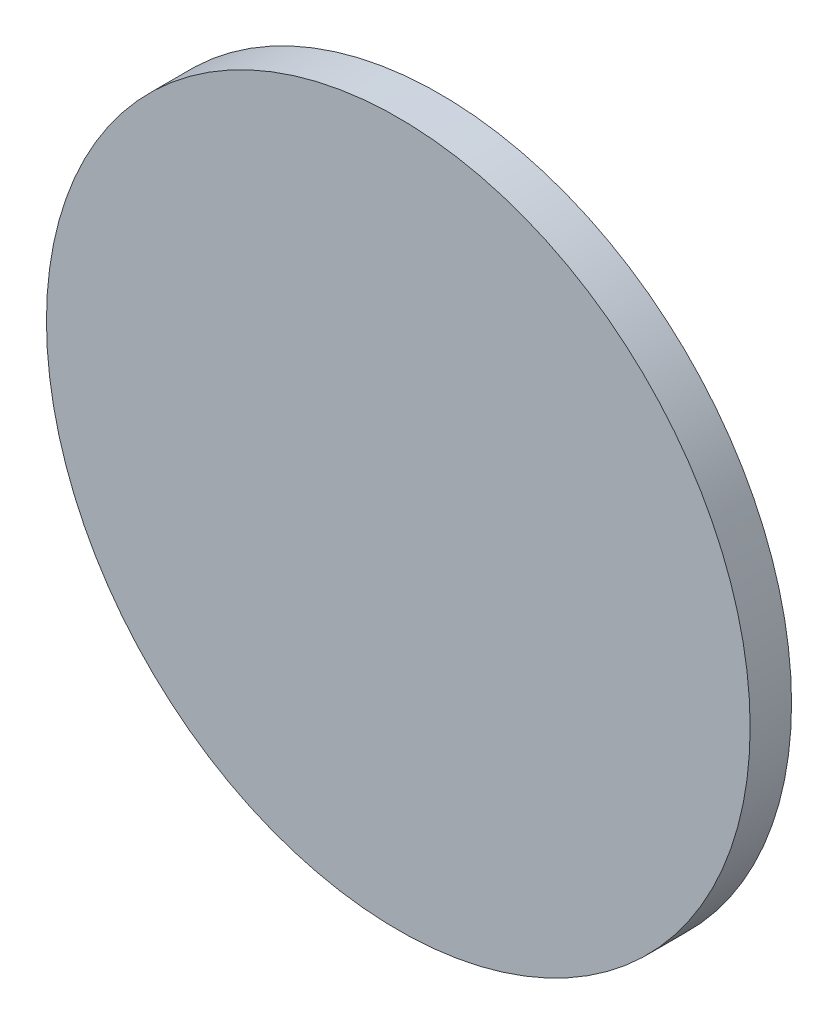
SolidWorks part; units mm, degrees
ref_plane "Front Plane" through (0, 0, 0) normal (0, 0, 1) x (1, 0, 0)
ref_plane "Top Plane" through (0, 0, 0) normal (0, 1, 0) x (1, 0, 0)
ref_plane "Right Plane" through (0, 0, 0) normal (1, 0, 0) x (0, 0, -1)
sketch "Sketch2" plane through (0, 0, 0) normal (0, 0, 1) x (1, 0, 0)
  circle A0 centre (0, 0) radius 25.5
  dimension "D1" = 51
extrude "Boss-Extrude1" add sketch "Sketch2" along normal blind 3
